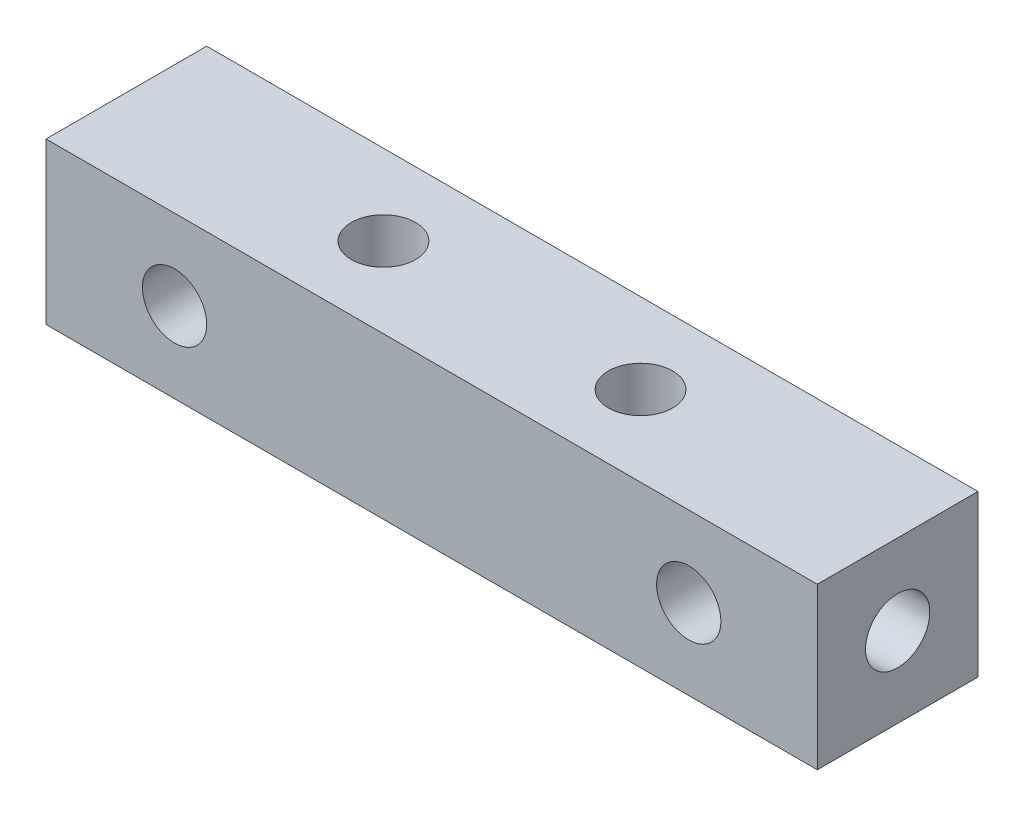
SolidWorks part; units mm, degrees
ref_plane "前视基准面" through (0, 0, 0) normal (0, 0, 1) x (1, 0, 0)
ref_plane "上视基准面" through (0, 0, 0) normal (0, 1, 0) x (1, 0, 0)
ref_plane "右视基准面" through (0, 0, 0) normal (1, 0, 0) x (0, 0, -1)
other "Configuration Table"
sketch "草图1" plane through (0, 0, 0) normal (0, 1, 0) x (1, 0, 0)
  line L1 (-24, 5) -> (24, 5)
  line L2 (-24, 5) -> (-24, -5)
  line L3 (-24, -5) -> (24, -5)
  line L4 (24, 5) -> (24, -5)
  line L5 (-24, 5) -> (24, -5) construction
  line L6 (-24, -5) -> (24, 5) construction
  point P0 (0, 0)
  dimension "D1" = 10
  dimension "D2" = 48
extrude "凸台-拉伸1" add sketch "草图1" along normal blind 10
sketch "草图2" plane through (0, 0, 5) normal (0, 0, 1) x (1, 0, 0)
  line L0 (-16, 5) -> (16, 5) construction
  line L1 (0, 5) -> (0, 0) construction
  circle A0 centre (-16, 5) radius 2
  circle A1 centre (16, 5) radius 2
  dimension "D2" = 4
  dimension "D1" = 5
  dimension "D3" = 32
extrude "切除-拉伸1" cut sketch "草图2" against normal blind 10
sketch "草图3" plane through (0, 10, 0) normal (0, 1, 0) x (1, 0, 0)
  line L0 (-8, 0) -> (8, 0) construction
  circle A0 centre (-8, 0) radius 2
  circle A1 centre (8, 0) radius 2
  point P4 (0, 0)
  dimension "D2" = 4
  dimension "D1" = 16
extrude "切除-拉伸2" cut sketch "草图3" against normal blind 10
sketch "草图4" plane through (-24, 0, 0) normal (-1, 0, 0) x (0, 0, 1)
  line L0 (0, 5) -> (5, 5) construction
  line L1 (5, 10) -> (5, 0) construction
  line L2 (0, 5) -> (0, 0) construction
  line L3 (-5, 0) -> (5, 0) construction
  circle A0 centre (0, 5) radius 2
  dimension "D1" = 4
extrude "切除-拉伸3" cut sketch "草图4" against normal blind 8
mirror "镜向1" about plane through (0, 0, 0) normal (1, 0, 0) of "切除-拉伸3"
